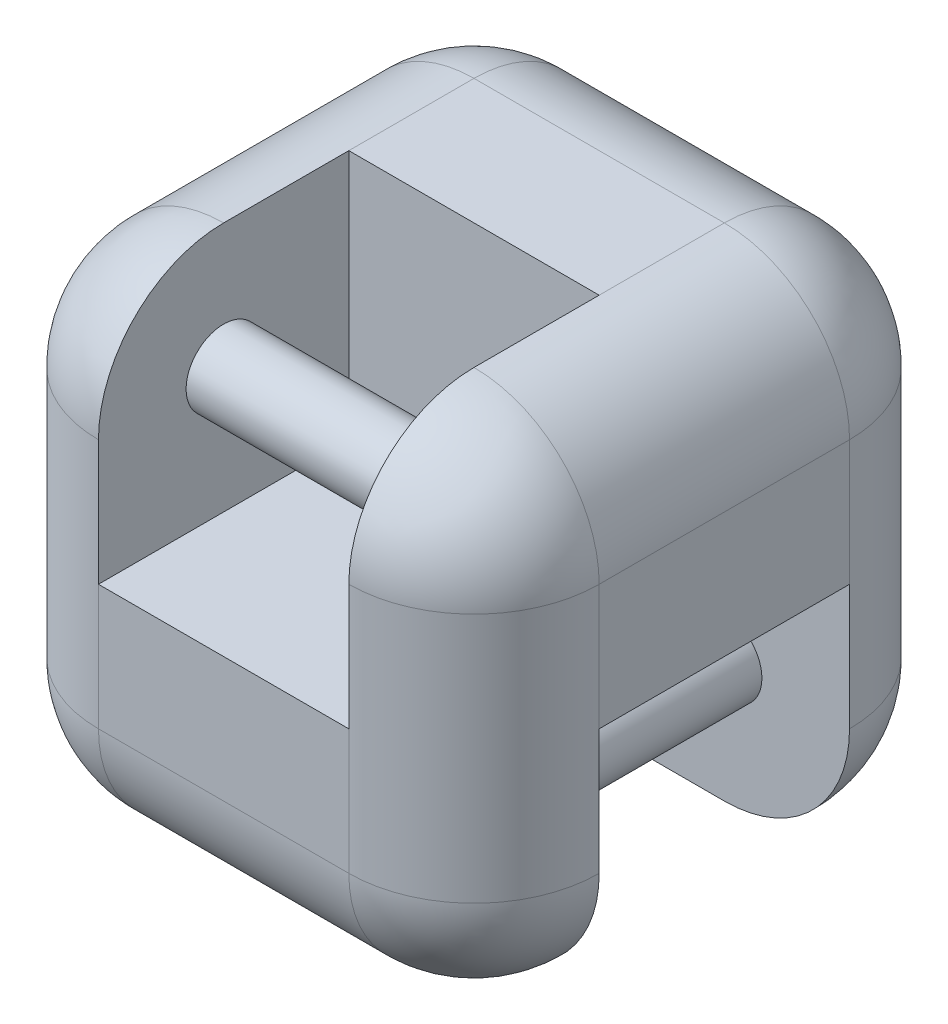
SolidWorks part; units mm, degrees
ref_plane "前视基准面" through (0, 0, 0) normal (0, 0, 1) x (1, 0, 0)
ref_plane "上视基准面" through (0, 0, 0) normal (0, 1, 0) x (1, 0, 0)
ref_plane "右视基准面" through (0, 0, 0) normal (1, 0, 0) x (0, 0, -1)
sketch "草图1" plane through (0, 0, 0) normal (0, 0, 1) x (1, 0, 0)
  line L1 (-23.4081, 37.1656) -> (-3.4081, 37.1656)
  line L2 (-23.4081, 37.1656) -> (-23.4081, 17.1656)
  line L3 (-23.4081, 17.1656) -> (-3.4081, 17.1656)
  line L4 (-3.4081, 37.1656) -> (-3.4081, 17.1656)
  dimension "D1" = 20
extrude "凸台-拉伸1" add sketch "草图1" along normal blind 20
fillet "圆角1" radius 5 12 edges at (-23.4081, 27.1656, 0) (-23.4081, 17.1656, 10) (-13.4081, 17.1656, 0) (-3.4081, 27.1656, 0) (-13.4081, 37.1656, 0) (-23.4081, 37.1656, 10) (-23.4081, 27.1656, 20) (-13.4081, 37.1656, 20) (-3.4081, 37.1656, 10) (-3.4081, 17.1656, 10) (-3.4081, 27.1656, 20) (-13.4081, 17.1656, 20)
ref_plane "基准面1" through (-8.4081, 0, 0) normal (-1, 0, 0) x (0, 0, 1)
sketch "草图2" plane through (-8.4081, 0, 0) normal (-1, 0, 0) x (0, 0, 1)
  line L1 (10, 27.1656) -> (20, 27.1656)
  line L2 (10, 27.1656) -> (10, 37.1656)
  line L3 (10, 37.1656) -> (20, 37.1656)
  line L4 (20, 27.1656) -> (20, 37.1656)
  line L5 (10, 27.1656) -> (20, 37.1656) construction
  line L6 (10, 37.1656) -> (20, 27.1656) construction
  point P0 (15, 32.1656)
extrude "切除-拉伸1" cut sketch "草图2" along normal blind 10
ref_plane "基准面2" through (0, 0, 5) normal (0, 0, 1) x (1, 0, 0)
sketch "草图3" plane through (0, 0, 5) normal (0, 0, 1) x (1, 0, 0)
  line L13 (-13.4081, 27.1656) -> (-3.4081, 27.1656)
  line L14 (-13.4081, 27.1656) -> (-13.4081, 17.1656)
  line L15 (-13.4081, 17.1656) -> (-3.4081, 17.1656)
  line L16 (-3.4081, 27.1656) -> (-3.4081, 17.1656)
  line L17 (-13.4081, 27.1656) -> (-3.4081, 17.1656) construction
  line L18 (-13.4081, 17.1656) -> (-3.4081, 27.1656) construction
  point P0 (-8.4081, 22.1656)
extrude "切除-拉伸2" cut sketch "草图3" along normal blind 10
sketch "草图4" plane through (-8.4081, 0, 0) normal (-1, 0, 0) x (0, 0, 1)
  circle A0 centre (15, 32.1656) radius 1.5
  dimension "D1" = 3
extrude "凸台-拉伸2" add sketch "草图4" along normal blind 10 separate body
sketch "草图5" plane through (0, 0, 5) normal (0, 0, 1) x (1, 0, 0)
  circle A0 centre (-8.4081, 22.1656) radius 1.5
  dimension "D1" = 3
extrude "凸台-拉伸3" add sketch "草图5" along normal blind 10 separate body
